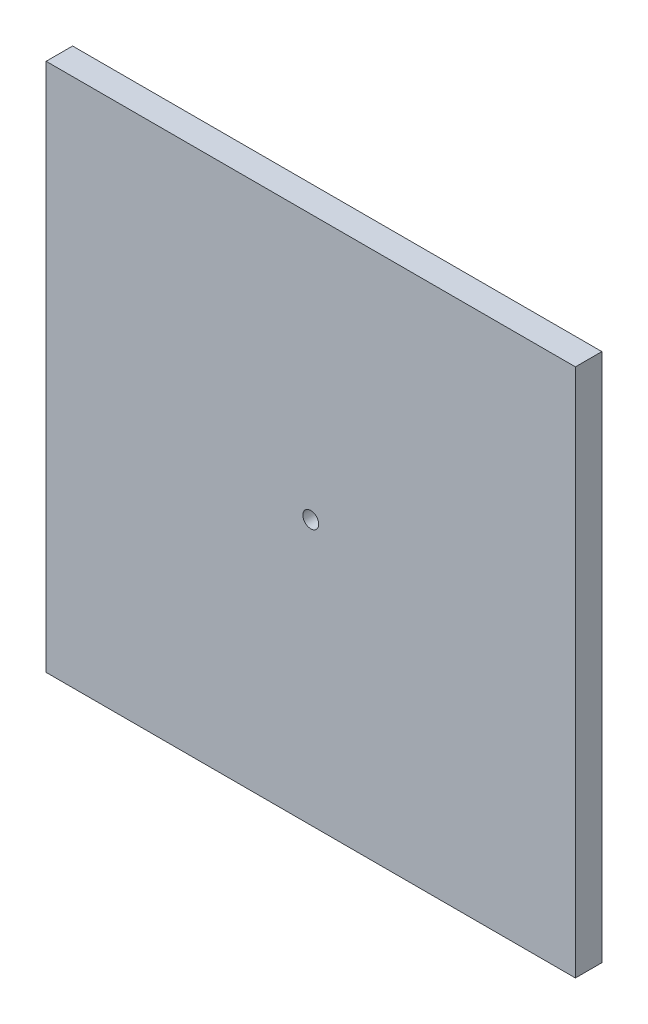
SolidWorks part; units mm, degrees
ref_plane "Front Plane" through (0, 0, 0) normal (0, 0, 1) x (1, 0, 0)
ref_plane "Top Plane" through (0, 0, 0) normal (0, 1, 0) x (1, 0, 0)
ref_plane "Right Plane" through (0, 0, 0) normal (1, 0, 0) x (0, 0, -1)
sketch "Sketch1" plane through (0, 0, 0) normal (0, 0, 1) x (1, 0, 0)
  line L1 (-50, 50) -> (50, 50)
  line L2 (-50, 50) -> (-50, -50)
  line L3 (-50, -50) -> (50, -50)
  line L4 (50, 50) -> (50, -50)
  circle A0 centre (0, 0) radius 50 construction
  circle A1 centre (0, 0) radius 1.5
  dimension "D1" = 100
  dimension "D2" = 3
extrude "Boss-Extrude1" add sketch "Sketch1" along normal blind 5
sketch "Sketch2" plane through (0, 0, 5) normal (0, 0, 1) x (1, 0, 0)
  circle A0 centre (0, 0) radius 1.5 construction
  point P0 (0, 0)
  point P1 (0, 0)
